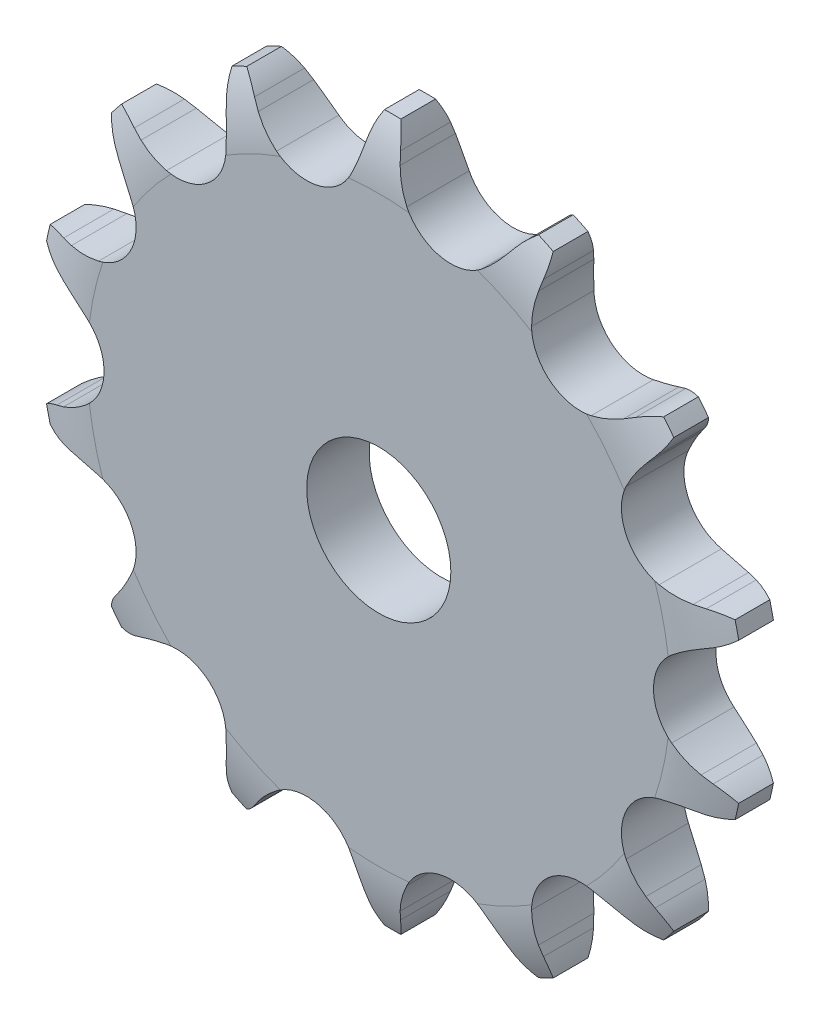
SolidWorks part; units mm, degrees
ref_plane "Front Plane" through (0, 0, 0) normal (0, 0, 1) x (1, 0, 0)
ref_plane "Top Plane" through (0, 0, 0) normal (0, 1, 0) x (1, 0, 0)
ref_plane "Right Plane" through (0, 0, 0) normal (1, 0, 0) x (0, 0, -1)
sketch "Sketch0" plane through (0, 0, 0) normal (0, 0, 1) x (1, 0, 0)
  line L0 (3, -13.1439) -> (0, 0) construction
  line L1 (0, 0) -> (8.4058, -10.5406) construction
  line L2 (0, 0) -> (-3, -13.1439) construction
  line L3 (3, -13.1439) -> (8.4058, -10.5406) construction
  line L4 (3, -13.1439) -> (-3, -13.1439) construction
  line L5 (5.4299, -12.7681) -> (5.1637, -12.429)
  line L6 (3, -13.1439) -> (0, -13.8286) construction
  line L7 (0.6477, -13.8596) -> (0.7405, -13.4386)
  line L8 (0, -13.1439) -> (0, -14.9439) construction
  line L9 (4.2569, -11.5268) -> (1.0362, -15.6704) construction
  line L10 (0, 0) -> (0, -13.1439) construction
  line L11 (5.1637, -12.429) -> (1.0362, -15.6704) construction
  line L12 (0, -14.9439) -> (0, -15.2174) construction
  line L13 (8.0454, -10.7141) -> (5.4299, -12.7681) construction
  circle A0 centre (0, 0) radius 14.9439 construction
  circle A1 centre (0, 0) radius 13.4819 construction
  arc A2 (-3.2453, -16.4063) -> (10.0424, -13.3734) centre (0, 0) ccw
  circle A3 centre (0, 0) radius 15.2174 construction
  circle A4 centre (3, -13.1439) radius 2 construction
  arc A7 (4.2569, -11.5268) -> (1.1659, -12.2323) centre (3, -13.1439) ccw
  circle A8 centre (3, -13.1439) radius 2.0481 construction
  arc A9 (5.4299, -12.7681) -> (10.0424, -13.3734) centre (8.0454, -10.7141) ccw
  arc A10 (5.1637, -12.429) -> (4.2569, -11.5268) centre (1.0362, -15.6704) ccw
  arc A11 (0.6477, -13.8596) -> (-3.2453, -16.4063) centre (-2.6, -13.1439) cw
  arc A12 (0.7405, -13.4386) -> (1.1659, -12.2323) centre (5.8656, -14.5681) cw
  dimension "D1" = 2.0481
  dimension "R" = 2.0481
sketch "Sketch1" plane through (0, 0, 0) normal (1, 0, 0) x (0, 0, -1)
  line L0 (1.3, 0) -> (-1.3, 0)
  line L1 (-1.3, 0) -> (-1.3, 12.1314)
  line L2 (-1.3, 13.4819) -> (0, 13.4819) construction
  line L3 (-0.6, 14.9439) -> (0.6, 14.9439)
  line L5 (1.3, 12.1314) -> (1.3, 0)
  line L7 (0, 14.9439) -> (0, 0) construction
  line L8 (-1.3, 12.1314) -> (1.3, 12.1314) construction
  line L9 (0, 14.9439) -> (0, -14.9439) construction
  line L10 (-1.3, 12.1314) -> (-1.3, 14.9439) construction
  line L11 (-1.3, 14.9439) -> (-0.6, 14.9439) construction
  line L12 (0.6, 14.9439) -> (1.3, 14.9439) construction
  line L13 (1.3, 14.9439) -> (1.3, 12.1314) construction
  line L14 (0, 0) -> (-6.4008, 0) construction
  line L15 (-1.3, 13.4819) -> (-1.3, 9.3819) construction
  line L22 (1.3, 0) -> (-8.7, 0) construction
  line L24 (-1.3, 0) -> (-1.3, 9.3819) construction
  arc A0 (-0.6, 14.9439) -> (-1.3, 12.1314) centre (4.7, 12.1314) ccw
  arc A1 (0.6, 14.9439) -> (1.3, 12.1314) centre (-4.7, 12.1314) cw
  dimension "R" = 6
revolve "Revolve1" add sketch "Sketch1" angle 360 mid plane about L0
extrude "Cut-Extrude1" cut sketch "Sketch0" against normal through all and the other way through all
pattern_circular "CirPattern1" count 14 over 360 about axis through (0, 0, 0) along (0, 0, 1) of "Cut-Extrude1"
sketch "Sketch2" plane through (0, 0, 0) normal (0, 0, 1) x (1, 0, 0)
  circle A0 centre (0, 0) radius 3 construction
  circle A1 centre (0, 0) radius 10
  circle A2 centre (0, 0) radius 14.7 construction
  dimension "Bore" = 6
  dimension "Hub Dia." = 20
  dimension "OD" = 29.4
extrude "Boss-Extrude1" add sketch "Sketch2" along normal up to vertex (8.7 mm away) from surface at 1.3 starting at face at (0, 0, 1.3)
sketch "Sketch3" plane through (0, 0, 0) normal (0, 0, 1) x (1, 0, 0)
  circle A0 centre (0, 0) radius 3 construction
  circle A1 centre (0, 0) radius 3
extrude "Cut-Extrude2" cut sketch "Sketch3" along normal through all and the other way through all
sketch "Sketch4" plane through (0, 0, 0) normal (1, 0, 0) x (0, 0, -1)
  line L0 (-8.7, 10) -> (-8.7, 9.5)
  line L1 (-1.3, 14.9439) -> (-3.25, 14.9439)
  line L2 (-1.3, 14.9439) -> (-1.3, 9.3819)
  line L3 (-1.3, 9.3819) -> (-3.25, 9.3819)
  line L4 (-3.25, 14.9439) -> (-3.25, 9.3819)
  line L9 (-8.7, 9.5) -> (-8.2, 10)
  line L10 (-8.2, 10) -> (-8.7, 10)
  dimension "C" = 0.5
  dimension "D3" = 1.95
revolve "Cut-Revolve1" cut sketch "Sketch4" angle 360 mid plane about L22
sketch "Sketch5" plane through (0, 0, 0) normal (0, 0, 1) x (1, 0, 0)
  circle A0 centre (0, 0) radius 14.7 construction
  circle A1 centre (0, 0) radius 14.7
extrude "Cut-Extrude3" cut sketch "Sketch5" against normal through all and the other way through all flip side to cut
sketch "Sketch6" plane through (0, 0, 1.3) normal (0, 0, 1) x (1, 0, 0)
  circle A0 centre (0, 0) radius 11.192
extrude "Cut-Extrude4" cut sketch "Sketch6" along normal blind 10
equation "\"360/N@Sketch0\" = 360/\"Teeth@CirPattern1\""
equation "\"Ds@Sketch0\" = 1.005 * \"Dr@Sketch0\" + ( 0.003 * 25.4 ) "
equation "\"R@Sketch0\" = 1/2 * \"Ds@Sketch0\""
equation "\"A@Sketch0\" = 35 +  ( 60 / \"Teeth@CirPattern1\" ) "
equation "\"B@Sketch0\" = 18 -  ( 56 / \"Teeth@CirPattern1\" )"
equation "\"ac@Sketch0\" = 0.8 * \"Dr@Sketch0\""
equation "\"ab@Sketch0\" = 1.4 * \"Dr@Sketch0\""
equation "\"J@Sketch0\" = 0.3 * \"Pitch@Sketch0\""
equation "\"D3@Sketch4\" = \"t@Sketch1\" * 3 / 4"
